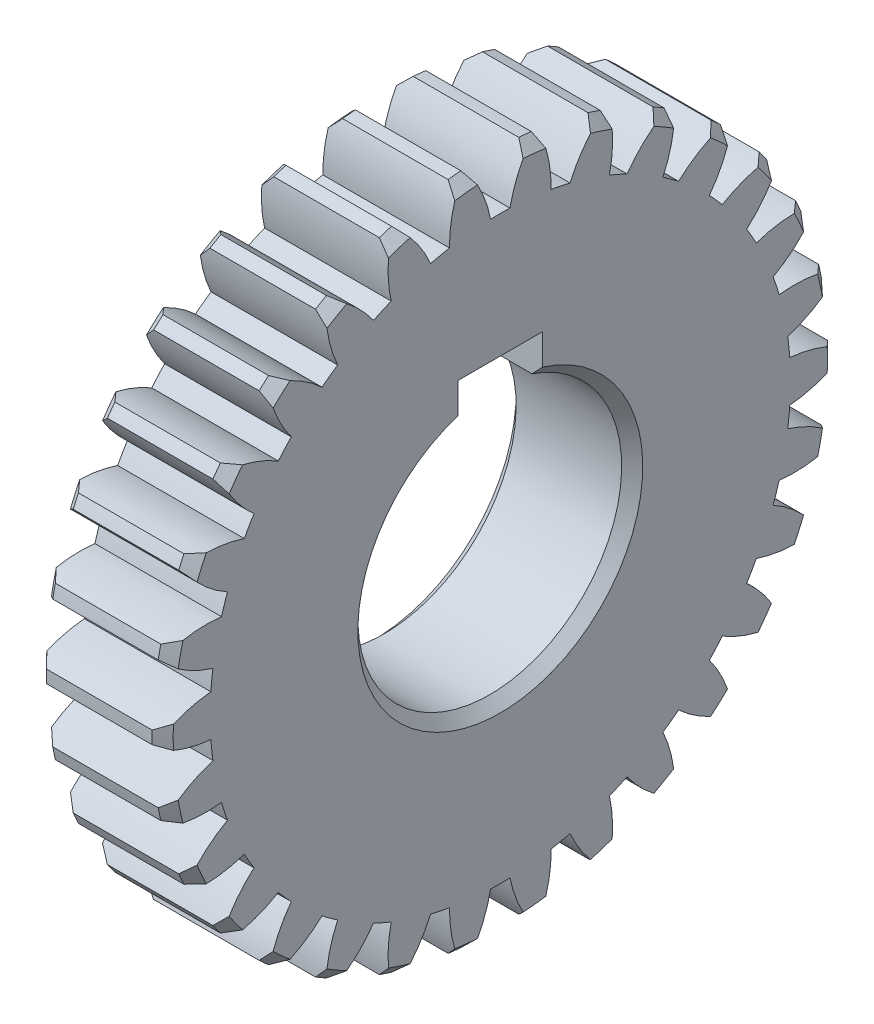
SolidWorks part; units mm, degrees
ref_plane "Plane1" through (0, 0, 0) normal (0, 0, 1) x (1, 0, 0)
ref_plane "Plane2" through (0, 0, 0) normal (0, 1, 0) x (1, 0, 0)
ref_plane "Plane3" through (0, 0, 0) normal (1, 0, 0) x (0, 0, -1)
sketch "HoldingSke" plane through (0, 0, 0) normal (0, 1, 0) x (1, 0, 0)
  line L0 (0, 0) -> (0.433, -0.25)
  line L1 (-15, 0) -> (100, 0) construction
  line L2 (0, 0) -> (-2.1039, 2.3779)
  line L3 (0, 0) -> (-11.863, 4.5341)
  line L4 (0, 0) -> (7.479, 4.318)
  line L5 (0, 0) -> (-46.8476, -17.4728)
  line L6 (0, 0) -> (-9.9476, -6.7116)
  line L7 (-2.1039, 2.3779) -> (8.6586, 51.2059)
  line L8 (-76.2, 54.61) -> (-72.9, 54.61)
  line L9 (-71.009, 38.7566) -> (-53.1078, 45.2721)
  line L10 (-76.2, 71.12) -> (104.1128, 71.12)
  line L11 (0, 0) -> (-12, 0)
  line L12 (-76.2, 101.6) -> (-76.133, 101.6)
  line L13 (24.9733, 27.94) -> (52.9518, 28.4284)
  line L14 (24.9733, 27.94) -> (24.9743, 27.94)
  line L15 (24.9733, 27.94) -> (100.4006, 29.5858)
  line L16 (-63.627, -2) -> (-12.827, -2)
  circle A0 centre (0, 0) radius 12.5
  circle A1 centre (0, 0) radius 27.499
  circle A2 centre (0, 0) radius 37.5
  circle A3 centre (0, 0) radius 12.5
  dimension "MHD" = 54.998
  dimension "Hub_dia" = 75
  dimension "Bore" = 25
  dimension "MBD" = 25
  dimension "Num_teeth" = 30
  dimension "Pitch" = 0.5
  dimension "Overall_len" = 50
  dimension "Show_teeth" = 30
  dimension "Thickness" = 12
  dimension "OAL" = 50.0001
  dimension "T_dim" = 3.3
  dimension "Ap" = 20
  dimension "H" = 19.05
  dimension "Pitch_radius" = 180.3128
  dimension "Width" = 12
  dimension "Backlash" = 0.067
  dimension "Addendum_fac" = 1
  dimension "Dedendum_fac" = 1.25
  dimension "Clearance_fac" = 0.25
  dimension "Dedendum_add" = 0.001
  dimension "Module" = 2
sketch "BasProSke" plane through (0, 0, 0) normal (0, 1, 0) x (1, 0, 0)
  line L0 (-10, 0) -> (60, 0) construction
  line L1 (0, 0) -> (0, 32)
  line L2 (0, 0) -> (12, 0)
  line L3 (12, 0) -> (12, 32)
  line L4 (12, 32) -> (0, 32)
  dimension "Thickness" = 12
  dimension "Diameter" = 64
revolve "Base-Revolve" add sketch "BasProSke" angle 360 about L0
sketch "TooCutSke" plane through (0, 0, 0) normal (1, 0, 0) x (0, 0, -1)
  line L1 (0, 0) -> (0, 107) construction
  line L2 (0, 0) -> (-1.6873, 29.9525) construction
  line L3 (0, 0) -> (-6.2643, 59.6013) construction
  line L4 (-1.6873, 29.9525) -> (-3.1322, 29.8007) construction
  arc A0 (0.9186, 27.4837) -> (-0.9186, 27.4837) centre (0, 0) ccw
  arc A1 (2.7618, 31.9061) -> (-2.7618, 31.9061) centre (0, 0) ccw
  circle A2 centre (0, 0) radius 30 construction
  circle A3 centre (0, 0) radius 28.1908 construction
  arc A4 (-0.9186, 27.4837) -> (-2.7618, 31.9061) centre (-12.6936, 25.1712) ccw
  arc A5 (2.7618, 31.9061) -> (0.9186, 27.4837) centre (12.6936, 25.1712) ccw
  dimension "Root_dia" = 54.998
  dimension "Overcut_dia" = 64.0508
  dimension "Pitch_dia" = 60
  dimension "Base_dia" = 56.3816
  dimension "Flank_rad" = 12
  dimension "Half_ang" = 6
  dimension "Half_CT" = 1.4528
extrude "ToothCut" cut sketch "TooCutSke" along normal through all
fillet "Breaks" [suppressed] radius 0.04
fillet "RootFillets" [suppressed] radius 0.501
pattern_circular "TeethCuts" count 30 every 12 about axis through (-10, 0, 0) along (1, 0, 0) of "ToothCut", "RootFillets", "Breaks"
sketch "HubNeaOneSke" plane through (0, 0, 0) normal (-1, 0, 0) x (0, 0, 1)
  circle A0 centre (0, 0) radius 27.499
  dimension "Diameter" = 54.998
extrude "HubNearOne" [suppressed] add sketch "HubNeaOneSke" along normal blind 38.0001
sketch "HubNeaBotSke" plane through (0, 0, 0) normal (-1, 0, 0) x (0, 0, 1)
  circle A0 centre (0, 0) radius 27.499
  dimension "Diameter" = 54.998
extrude "HubNearBoth" [suppressed] add sketch "HubNeaBotSke" along normal blind 19
ref_plane "FarPln" through (12, 0, 0) normal (1, 0, 0) x (0, 0, -1)
sketch "HubFarSke" plane through (12, 0, 0) normal (1, 0, 0) x (0, 0, -1)
  circle A0 centre (0, 0) radius 27.499
  dimension "Diameter" = 54.998
extrude "HubFar" [suppressed] add sketch "HubFarSke" along normal blind 19
sketch "BorSke" plane through (0, 0, 0) normal (1, 0, 0) x (0, 0, -1)
  circle A0 centre (0, 0) radius 12.5
  dimension "Diameter" = 25
extrude "Bore" cut sketch "BorSke" along normal mid plane 100.0001
sketch "KeySke" plane through (0, 0, 0) normal (1, 0, 0) x (0, 0, -1)
  line L0 (-4, 0) -> (-4, 15.8)
  line L1 (-4, 15.8) -> (4, 15.8)
  line L2 (4, 15.8) -> (4, 0)
  line L3 (0, 0) -> (0, 34) construction
  line L4 (-4, 0) -> (4, 0)
  dimension "Offset" = 15.8
  dimension "Width" = 8
extrude "Keyway" cut sketch "KeySke" along normal mid plane 100.0001
pattern_circular "Keyway2" [suppressed] count 2 every 90 about axis through (-10, 0, 0) along (1, 0, 0)
chamfer "Chamfer1" distance 1 angle 45 2 edges at (12, -12.5, 0) (0, -12.5, 0)
chamfer "Chamfer2" distance 1 angle 45 60 edges at (0, 6.6532, -31.3007) (0, 0, -32) (0, -6.6532, -31.3007) (0, -13.0156, -29.2335) (12, 31.8247, 3.3449) (12, 30.4338, 9.8885) (12, 27.7128, 16) (12, 23.7806, 21.4122) (12, 31.8247, -3.3449) (12, 30.4338, -9.8885) (12, 27.7128, -16) (12, 23.7806, -21.4122) (12, 18.8091, -25.8885) (12, 13.0156, -29.2335) (12, 6.6532, -31.3007) (12, 0, -32) (12, -6.6532, -31.3007) (12, -13.0156, -29.2335) (12, -18.8091, -25.8885) (12, -30.4338, -9.8885) (12, -23.7806, -21.4122) (12, -27.7128, -16) (12, 18.8091, 25.8885) (12, 13.0156, 29.2335) (12, 6.6532, 31.3007) (12, 0, 32) (12, -6.6532, 31.3007) (12, -13.0156, 29.2335) (12, -18.8091, 25.8885) (12, -23.7806, 21.4122) (12, -27.7128, 16) (12, -30.4338, 9.8885) (12, -31.8247, 3.3449) (12, -31.8247, -3.3449) (0, 31.8247, 3.3449) (0, 30.4338, 9.8885) (0, 27.7128, 16) (0, 23.7806, 21.4122) (0, 18.8091, 25.8885) (0, 13.0156, 29.2335) (0, 6.6532, 31.3007) (0, 0, 32) (0, -6.6532, 31.3007) (0, -13.0156, 29.2335) (0, -18.8091, 25.8885) (0, -23.7806, 21.4122) (0, -27.7128, 16) (0, -30.4338, 9.8885) (0, -31.8247, 3.3449) (0, -31.8247, -3.3449) (0, -30.4338, -9.8885) (0, -27.7128, -16) (0, -23.7806, -21.4122) (0, -18.8091, -25.8885) (0, 31.8247, -3.3449) (0, 30.4338, -9.8885) (0, 27.7128, -16) (0, 23.7806, -21.4122) (0, 18.8091, -25.8885) (0, 13.0156, -29.2335)
equation "' \"Module@HoldingSke\" = 6.35"
equation "' \"Num_teeth@HoldingSke\" = 12"
equation "' \"Ap@HoldingSke\" =  20"
equation "' \"Ap@HoldingSke\" = 20"
equation "' \"Width@HoldingSke\" = 0.5 * 25.4"
equation "' \"Hub_dia@HoldingSke\"= 1 * 25.4"
equation "' \"Hub_dia@HoldingSke\" = 1 * 25.4"
equation "' \"Overall_len@HoldingSke\" = 1.0 * 25.4"
equation "' \"Bore@HoldingSke\" = 0.75 * 25.4"
equation "' \"T_dim@HoldingSke\" = 0.1 * 25.4"
equation "' \"Width@KeySke\" = 0.25 * 25.4"
equation "' \"Show_teeth@HoldingSke\" = 13"
equation "' \"Backlash@HoldingSke\" = 0.009 * 25.4"
equation "' \"Addendum_fac@HoldingSke\" = 1.0"
equation "' \"Dedendum_fac@HoldingSke\" = 1.25"
equation "' \"Dedendum_add@HoldingSke\" = 0.00005 * 25.4"
equation "' \"Clearance_fac@HoldingSke\" = 0.25"
equation "\"Pitch@HoldingSke\" = 1 / \"Module@HoldingSke\""
equation "\"Overcut_dia@TooCutSke\" = (\"Num_teeth@HoldingSke\" + 2 * \"Addendum_fac@HoldingSke\") / \"Pitch@HoldingSke\" + 0.002 * 25.4"
equation "\"Pitch_dia@TooCutSke\" = \"Num_teeth@HoldingSke\" / \"Pitch@HoldingSke\""
equation "\"Base_dia@TooCutSke\" = \"Num_teeth@HoldingSke\" / \"Pitch@HoldingSke\" * cos((\"Ap@HoldingSke\"  * 3.14159265 / 180))"
equation "\"Root_dia@TooCutSke\" = (\"Num_teeth@HoldingSke\" + 2) / \"Pitch@HoldingSke\" - 2 * (\"Addendum_fac@HoldingSke\" + \"Dedendum_fac@HoldingSke\") / \"Pitch@HoldingSke\" - \"Dedendum_add@HoldingSke\" * 2"
equation "\"Half_ang@TooCutSke\" = 180 / \"Num_teeth@HoldingSke\""
equation "\"Half_CT@TooCutSke\" = \"Num_teeth@HoldingSke\" / \"Pitch@HoldingSke\" * sin((3.14159265 / 2 / \"Num_teeth@HoldingSke\")) / 2 - 7 * \"Backlash@HoldingSke\" / 4"
equation "\"Flank_rad@TooCutSke\" = \"Num_teeth@HoldingSke\" / \"Pitch@HoldingSke\" / 5"
equation "\"Radius@RootFillets\" = \"Clearance_fac@HoldingSke\" / \"Pitch@HoldingSke\" + \"Dedendum_add@HoldingSke\""
equation "\"Break_rad@Breaks\" = 0.02 / \"Pitch@HoldingSke\""
equation "\"Thickness@HoldingSke\" = \"Width@HoldingSke\""
equation "\"OAL@HoldingSke\" = \"Thickness@HoldingSke\""
equation "\"MHD@HoldingSke\" = (\"Num_teeth@HoldingSke\" + 2) / \"Pitch@HoldingSke\" - 2 * (\"Addendum_fac@HoldingSke\" + \"Dedendum_fac@HoldingSke\")  / \"Pitch@HoldingSke\" - \"Dedendum_add@HoldingSke\" * 2"
equation "\"MBD@HoldingSke\" = (\"Num_teeth@HoldingSke\" + 2) / \"Pitch@HoldingSke\" - 2 * (\"Addendum_fac@HoldingSke\" + \"Dedendum_fac@HoldingSke\")  / \"Pitch@HoldingSke\" - \"Dedendum_add@HoldingSke\" * 2 - 0.002 * 25.4"
equation "\"MHD@HoldingSke\" = ((sgn( \"MHD@HoldingSke\" - \"Hub_dia@HoldingSke\" )-1)*( \"MHD@HoldingSke\" - \"Hub_dia@HoldingSke\" ))/-2+ \"Hub_dia@HoldingSke\""
equation "\"MBD@HoldingSke\" = ((sgn( \"MBD@HoldingSke\" - \"Bore@HoldingSke\" )-1)*( \"MBD@HoldingSke\" - \"Bore@HoldingSke\" ))/-2+ \"Bore@HoldingSke\""
equation "\"OAL@HoldingSke\" = ((sgn( \"OAL@HoldingSke\" - \"Overall_len@HoldingSke\" )+1)*( \"OAL@HoldingSke\" - \"Overall_len@HoldingSke\" ))/2 + \"Overall_len@HoldingSke\" + 0.000002 * 25.4"
equation "\"Num_teeth@TeethCuts\" = int( \"Show_teeth@HoldingSke\" ) + 1"
equation "\"Num_teeth@TeethCuts\" = ((sgn( \"Num_teeth@TeethCuts\" - \"Num_teeth@HoldingSke\" )-1)*( \"Num_teeth@TeethCuts\" - \"Num_teeth@HoldingSke\" ))/-2+ \"Num_teeth@HoldingSke\""
equation "\"Num_teeth@TeethCuts\" = ((sgn( \"Num_teeth@TeethCuts\" - 2.0)+1)*( \"Num_teeth@TeethCuts\" - 2.0))/2 +2.0"
equation "\"Angle@TeethCuts\" = 360.0 / \"Num_teeth@HoldingSke\""
equation "\"Diameter@BasProSke\" = (\"Num_teeth@HoldingSke\" + 2 * \"Addendum_fac@HoldingSke\") / \"Pitch@HoldingSke\""
equation "\"Thickness@BasProSke\"  = \"Thickness@HoldingSke\""
equation "' \"Fillet_rad@BasProSke\" =  \"Thickness@HoldingSke\" * 0.05"
equation "' \"Fillet_rad@BasProSke\" = \"Thickness@HoldingSke\" * 0.05"
equation "\"MHD@HoldingSke\" = ((sgn( \"MHD@HoldingSke\" - \"Root_dia@TooCutSke\" )-1)*( \"MHD@HoldingSke\" - \"Root_dia@TooCutSke\" ))/-2+ \"Root_dia@TooCutSke\""
equation "\"Diameter@HubNeaOneSke\" = \"MHD@HoldingSke\""
equation "\"Length@HubNearOne\" = \"OAL@HoldingSke\" - \"Thickness@BasProSke\""
equation "\"Diameter@HubNeaBotSke\" = \"MHD@HoldingSke\""
equation "\"Length@HubNearBoth\" = ( \"OAL@HoldingSke\" - \"Thickness@BasProSke\" ) / 2.0"
equation "\"Thickness@FarPln\" = \"Thickness@BasProSke\""
equation "\"Diameter@HubFarSke\" = \"MHD@HoldingSke\""
equation "\"Length@HubFar\" = ( \"OAL@HoldingSke\" - \"Thickness@BasProSke\" ) / 2.0"
equation "\"Diameter@BorSke\" = \"MBD@HoldingSke\""
equation "\"D1@Bore\" = \"OAL@HoldingSke\" * 2.0"
equation "\"D1@Keyway\" = \"OAL@HoldingSke\" * 2.0"
equation "\"Offset@KeySke\" = \"T_dim@HoldingSke\" + \"MBD@HoldingSke\" / 2.0"
